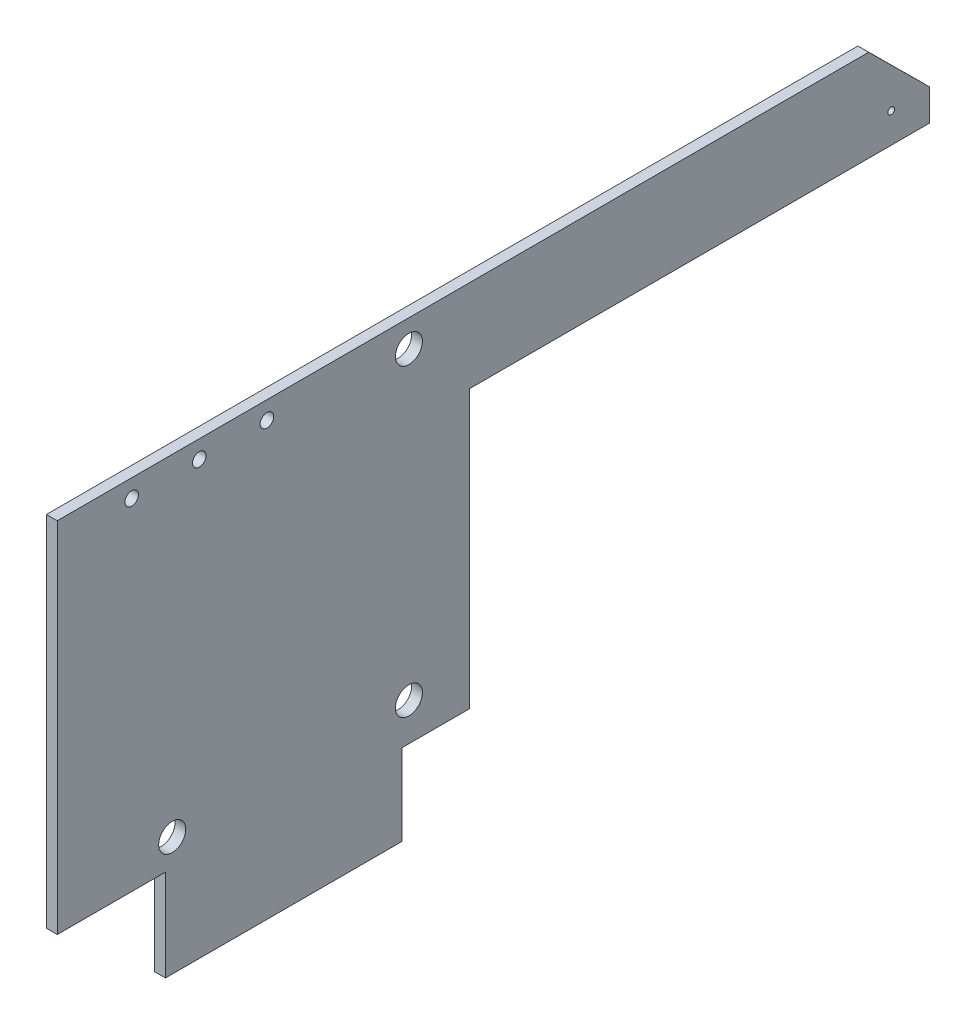
SolidWorks part; units mm, degrees
ref_plane "Front Plane" through (0, 0, 0) normal (0, 0, 1) x (1, 0, 0)
ref_plane "Top Plane" through (0, 0, 0) normal (0, 1, 0) x (1, 0, 0)
ref_plane "Right Plane" through (0, 0, 0) normal (1, 0, 0) x (0, 0, -1)
sketch "Sketch1" plane through (0, 0, 0) normal (1, 0, 0) x (0, 0, -1)
  line L0 (3, 11) -> (3, 64)
  line L1 (3, 64) -> (123, 64)
  line L2 (123, 64) -> (132, 55.0634)
  line L3 (132, 55.0634) -> (132, 50.4234)
  line L4 (132, 50.4234) -> (64, 50.4234)
  line L5 (64, 50.4234) -> (64, 9.4361)
  line L6 (64, 9.4361) -> (54, 9.4361)
  line L7 (54, 9.4361) -> (54, -2.5639)
  line L8 (54, -2.5639) -> (19, -2.5639)
  line L9 (19, -2.5639) -> (19, 11)
  line L10 (19, 11) -> (3, 11)
  line L11 (125.3885, 53.8858) -> (129.2597, 57.7844) construction
  line L12 (129.2597, 57.7844) -> (114.1105, 42.5277) construction
  circle A0 centre (20, 15) radius 2
  circle A1 centre (55, 15) radius 2
  circle A2 centre (55, 60) radius 2
  circle A3 centre (14, 61.35) radius 1
  circle A4 centre (24, 61.35) radius 1
  circle A5 centre (34, 61.35) radius 1
  circle A6 centre (126.3282, 54.8322) radius 0.5
  circle A7 centre (14, 61.35) radius 0.5 construction
  circle A8 centre (24, 61.35) radius 0.5 construction
  circle A9 centre (34, 61.35) radius 0.5 construction
  circle A12 centre (55, 60) radius 2 construction
  circle A13 centre (55, 15) radius 2 construction
  circle A14 centre (20, 15) radius 2 construction
  circle A15 centre (126.3282, 54.8322) radius 0.5 construction
  dimension "D1" = 2
  dimension "D2" = 120
  dimension "D3" = 16
  dimension "D4" = 10
  dimension "D5" = 35
  dimension "D6" = 68
  dimension "D7" = 53
  dimension "D8" = 13.5639
  dimension "D9" = 40.9874
  dimension "D10" = 12
  dimension "D11" = 11
  dimension "D12" = 3
extrude "Boss-Extrude1" add sketch "Sketch1" along normal blind 1.6
